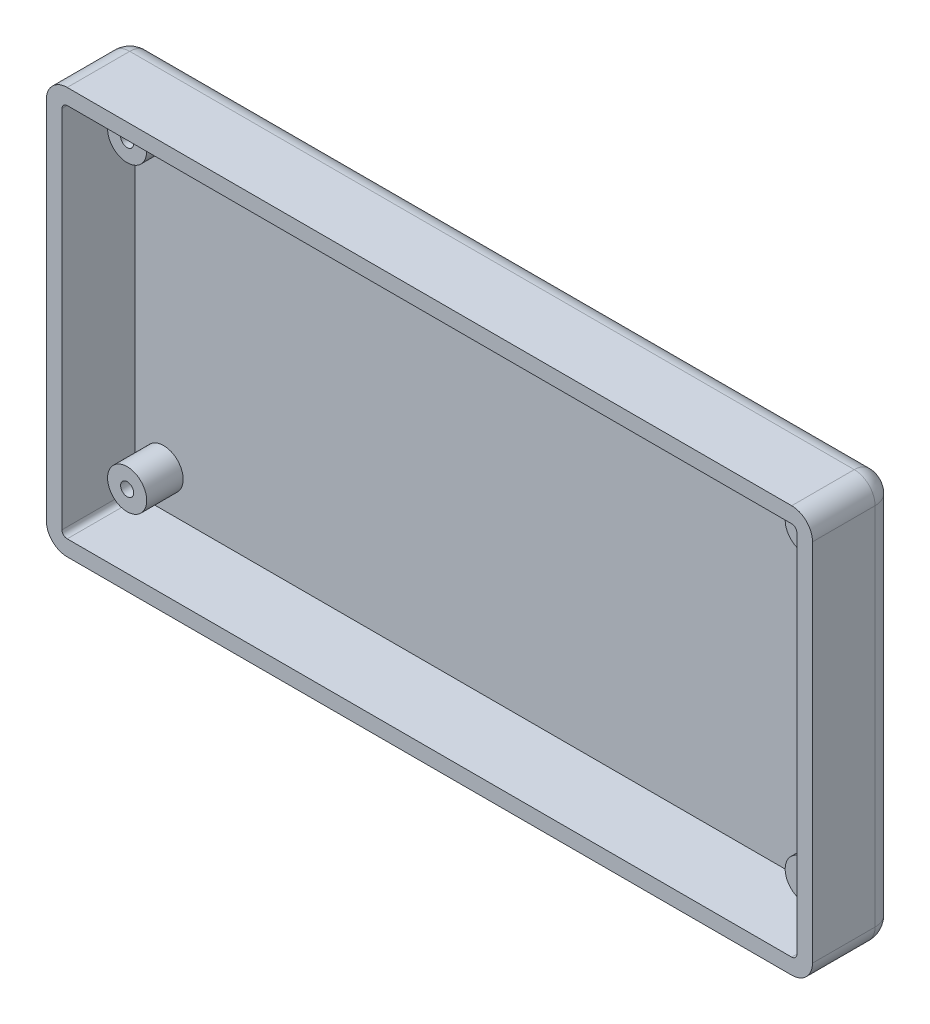
SolidWorks part; units mm, degrees
ref_plane "Front Plane" through (0, 0, 0) normal (0, 0, 1) x (1, 0, 0)
ref_plane "Top Plane" through (0, 0, 0) normal (0, 1, 0) x (1, 0, 0)
ref_plane "Right Plane" through (0, 0, 0) normal (1, 0, 0) x (0, 0, -1)
sketch "Sketch1" plane through (0, 0, 0) normal (0, 0, 1) x (1, 0, 0)
  line L1 (-73.5, 39) -> (73.5, 39)
  line L2 (-73.5, 39) -> (-73.5, -39)
  line L3 (-73.5, -39) -> (73.5, -39)
  line L4 (73.5, 39) -> (73.5, -39)
  line L5 (-73.5, 39) -> (73.5, -39) construction
  line L6 (-73.5, -39) -> (73.5, 39) construction
  point P0 (0, 0)
  dimension "D1" = 78
  dimension "D2" = 147
extrude "Boss-Extrude1" add sketch "Sketch1" along normal blind 16
fillet "Fillet1" radius 4 4 edges at (-73.5, -39, 8) (73.5, -39, 8) (73.5, 39, 8) (-73.5, 39, 8)
fillet "Fillet2" radius 4 8 edges at (-72.3284, 37.8284, 0) (0, 39, 0) (72.3284, 37.8284, 0) (73.5, 0, 0) (72.3284, -37.8284, 0) (0, -39, 0) (-72.3284, -37.8284, 0) (-73.5, 0, 0)
sketch "Sketch2" plane through (0, 0, 16) normal (0, 0, 1) x (1, 0, 0)
  line L24 (-70.5, 35) -> (-70.5, -35)
  line L25 (-69.5, -36) -> (69.5, -36)
  line L26 (70.5, -35) -> (70.5, 35)
  line L27 (69.5, 36) -> (-69.5, 36)
  line L28 (-70.5, 35) -> (-70.5, -35)
  line L29 (-69.5, -36) -> (69.5, -36)
  line L30 (70.5, -35) -> (70.5, 35)
  line L31 (69.5, 36) -> (-69.5, 36)
  arc A20 (-69.5, 36) -> (-70.5, 35) centre (-69.5, 35) ccw
  arc A21 (-70.5, -35) -> (-69.5, -36) centre (-69.5, -35) ccw
  arc A22 (69.5, -36) -> (70.5, -35) centre (69.5, -35) ccw
  arc A23 (70.5, 35) -> (69.5, 36) centre (69.5, 35) ccw
  arc A24 (-69.5, 36) -> (-70.5, 35) centre (-69.5, 35) ccw
  arc A25 (-70.5, -35) -> (-69.5, -36) centre (-69.5, -35) ccw
  arc A26 (69.5, -36) -> (70.5, -35) centre (69.5, -35) ccw
  arc A27 (70.5, 35) -> (69.5, 36) centre (69.5, 35) ccw
  dimension "D1" = 3
extrude "Cut-Extrude1" cut sketch "Sketch2" against normal offset from surface (14 mm away) 2 up to face at (0, 0, 0)
sketch "Sketch3" plane through (0, 0, 2) normal (0, 0, 1) x (1, 0, 0)
  line L0 (0, 0) -> (0, 46.8909) construction
  line L1 (0, 0) -> (-49.704, 0) construction
  circle A0 centre (-65, 29) radius 3.75
  circle A1 centre (-65, 29) radius 1.25
  circle A2 centre (65, 29) radius 1.25
  circle A3 centre (65, 29) radius 3.75
  circle A4 centre (65, -29) radius 1.25
  circle A5 centre (65, -29) radius 3.75
  circle A6 centre (-65, -29) radius 1.25
  circle A7 centre (-65, -29) radius 3.75
  dimension "D1" = 7.5
  dimension "D2" = 2.5
  dimension "D3" = 130
  dimension "D4" = 58
extrude "Boss-Extrude2" add sketch "Sketch3" along normal blind 7
